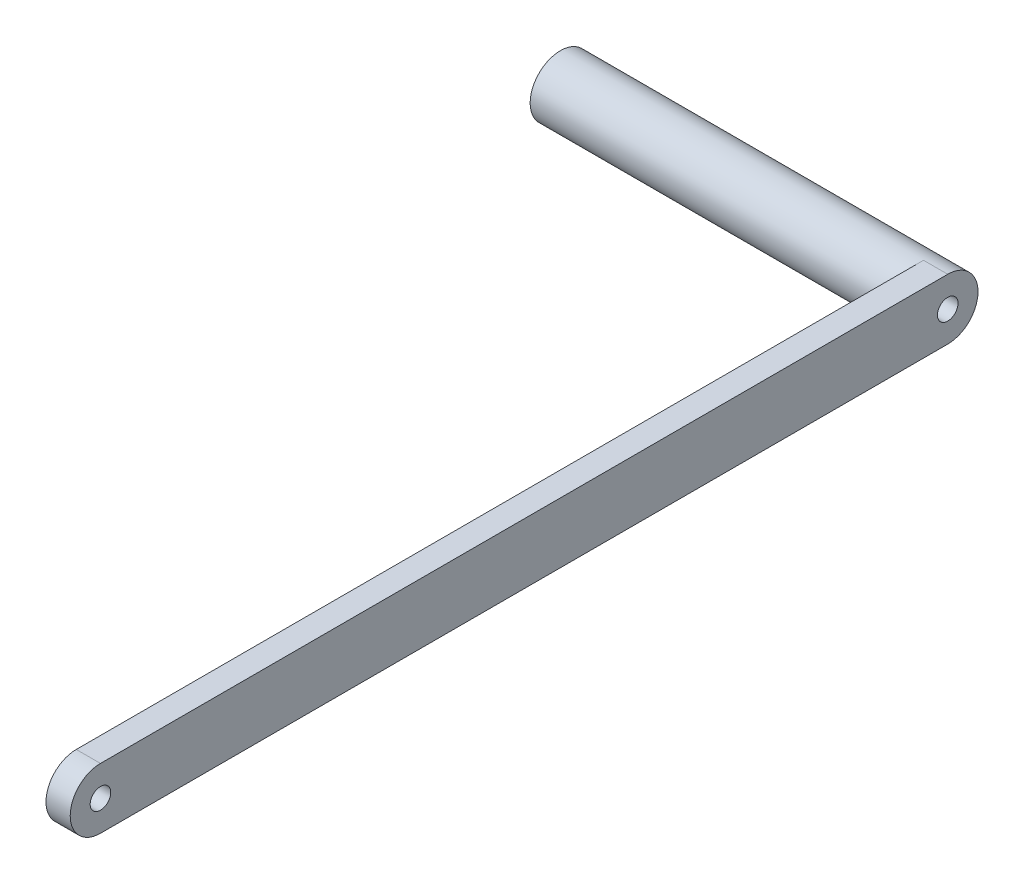
SolidWorks part; units mm, degrees
ref_plane "Plano frontal" through (0, 0, 0) normal (0, 0, 1) x (1, 0, 0)
ref_plane "Plano superior" through (0, 0, 0) normal (0, 1, 0) x (1, 0, 0)
ref_plane "Plano direito" through (0, 0, 0) normal (1, 0, 0) x (0, 0, -1)
sketch "Esboço1" plane through (0, 0, 0) normal (1, 0, 0) x (0, 0, -1)
  line L0 (-35, 0) -> (35, 0) construction
  line L1 (-35, 2.5) -> (35, 2.5)
  line L2 (-35, -2.5) -> (35, -2.5)
  arc A0 (-35, 2.5) -> (-35, -2.5) centre (-35, 0) ccw
  arc A1 (35, -2.5) -> (35, 2.5) centre (35, 0) ccw
  point P2 (0, 0)
  dimension "D1" = 5
  dimension "D2" = 70
extrude "Ressalto-extrusão1" add sketch "Esboço1" along normal blind 2
sketch "Esboço2" plane through (0, 0, 0) normal (-1, 0, 0) x (0, 0, 1)
  circle A0 centre (-35, 0) radius 2.5
  arc A1 (-35, 2.5) -> (-35, -2.5) centre (-35, 0) ccw construction
extrude "Ressalto-extrusão2" add sketch "Esboço2" along normal blind 30
sketch "Esboço3" plane through (-30, 0, 0) normal (-1, 0, 0) x (0, 0, 1)
  circle A0 centre (-35, 0) radius 0.85
  circle A1 centre (-35, 0) radius 2.5 construction
  dimension "D1" = 1.7
extrude "Corte-extrusão1" cut sketch "Esboço3" against normal up to next
sketch "Esboço4" plane through (0, 0, 0) normal (-1, 0, 0) x (0, 0, 1)
  circle A0 centre (35, 0) radius 0.85
  arc A1 (35, -2.5) -> (35, 2.5) centre (35, 0) ccw construction
  dimension "D1" = 1.7
extrude "Corte-extrusão2" cut sketch "Esboço4" against normal up to next
